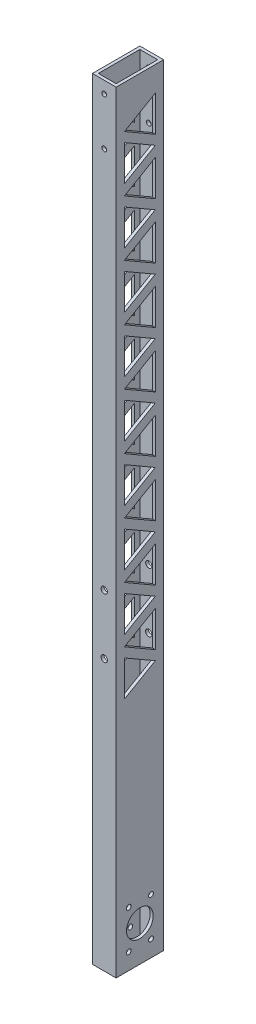
SolidWorks part; units mm, degrees
material "5052-O"
ref_plane "Front Plane" through (0, 0, 0) normal (0, 0, 1) x (1, 0, 0)
ref_plane "Top Plane" through (0, 0, 0) normal (0, 1, 0) x (1, 0, 0)
ref_plane "Right Plane" through (0, 0, 0) normal (1, 0, 0) x (0, 0, -1)
sketch "Sketch1" plane through (0, 0, 0) normal (0, 1, 0) x (1, 0, 0)
  line L0 (3.175, 3.175) -> (3.175, 47.625)
  line L1 (0, 0) -> (25.4, 0)
  line L2 (0, 0) -> (0, 50.8)
  line L3 (0, 50.8) -> (25.4, 50.8)
  line L4 (25.4, 0) -> (25.4, 50.8)
  line L5 (3.175, 47.625) -> (22.225, 47.625)
  line L6 (22.225, 3.175) -> (22.225, 47.625)
  line L7 (3.175, 3.175) -> (22.225, 3.175)
  dimension "D2" = 50.8
  dimension "D3" = 25.4
  dimension "D1" = 3.175
extrude "Boss-Extrude1" add sketch "Sketch1" along normal blind 825.5
sketch "Sketch2" plane through (0, 0, 0) normal (-1, 0, 0) x (0, 0, 1)
  line L0 (13.97, 0) -> (-13.97, 0) construction
  line L1 (-50.8, 825.5) -> (0, 825.5) construction
  circle A0 centre (-25.4, 38.1) radius 14.2875
  point P6 (-25.4, 825.5)
  dimension "D1" = 38.1
  dimension "D2" = 28.575
extrude "Cut-Extrude1" cut sketch "Sketch2" against normal through all
sketch "Sketch3" plane through (0, 0, 0) normal (0, 0, 1) x (1, 0, 0)
  line L0 (0, 825.5) -> (25.4, 825.5) construction
  line L1 (0, 825.5) -> (0, 0) construction
  circle A0 centre (12.7, 812.8) radius 2.5797
  circle A1 centre (12.7, 762) radius 2.5797
  dimension "D1" = 50.8
  dimension "D2" = 12.7
  dimension "D3" = 12.7
  dimension "D4" = 12.7
  dimension "D5" = 5.1594
  dimension "D6" = 5.1594
extrude "Cut-Extrude2" cut sketch "Sketch3" against normal through all
hole_wizard "13/64 (0.20313) Diameter Hole1" positions "Sketch4" profile "Sketch5" hole size "13/64" standard "ANSI Inch" end condition through all
sketch "Sketch4" plane through (25.4, 0, 0) normal (1, 0, 0) x (0, 0, -1)
  point P0 (37.3062, 58.7222)
  point P3 (13.4937, 58.7222)
  point P6 (37.3063, 17.4778)
  point P9 (13.4937, 17.4778)
sketch "Sketch5" plane through (25.4, 58.7222, -37.3062) normal (0, 1, 0) x (0, 0, -1)
  line L0 (0, 0) -> (0, 25.4)
  line L1 (0, 25.4) -> (2.5798, 25.4)
  line L2 (2.5798, 25.4) -> (2.5798, 0)
  line L5 (2.5798, 0) -> (0, 0)
  line L11 (0, -6.35) -> (0, 107.95) construction
  dimension "Thru Hole Dia." = 5.1595
  dimension "Thru Hole Depth" = 25.4
sketch "Sketch6" plane through (0, 0, -50.8) normal (0, 0, -1) x (-1, 0, 0)
  line L0 (-12.7, 825.5) -> (-12.7, 0) construction
  line L1 (-25.4, 825.5) -> (0, 825.5) construction
  line L2 (13.97, 0) -> (-13.97, 0) construction
  circle A0 centre (-12.7, 353.06) radius 3.3734
  circle A1 centre (-12.7, 289.56) radius 3.429
  dimension "D1" = 6.7469
  dimension "D2" = 6.858
  dimension "D4" = 63.5
  dimension "D3" = 472.44
extrude "Cut-Extrude3" cut sketch "Sketch6" against normal through all
sketch "Sketch7" plane through (25.4, 0, 0) normal (1, 0, 0) x (0, 0, -1)
  line L0 (25.4, 0) -> (25.4, 825.5) construction
  line L1 (41.91, 273.0641) -> (8.89, 292.1282)
  line L2 (8.89, 292.1282) -> (8.89, 254)
  line L3 (8.89, 254) -> (41.91, 273.0641)
  line L4 (13.97, 0) -> (-13.97, 0) construction
  line L5 (0, 825.5) -> (50.8, 825.5) construction
  line L6 (0, 0) -> (50.8, 0) construction
  line L7 (0, 825.5) -> (0, 0) construction
  line L8 (50.8, 825.5) -> (50.8, 0) construction
  line L9 (41.91, 321.4576) -> (8.89, 302.3935)
  line L10 (8.89, 302.3935) -> (41.91, 283.3294)
  line L11 (41.91, 283.3294) -> (41.91, 321.4576)
  circle A0 centre (19.8967, 273.0641) radius 11.0067 construction
  circle A1 centre (30.9033, 302.3935) radius 11.0067 construction
  point P11 (25.4, 311.9256)
  point P14 (25.4, 292.8614)
  point P16 (25.4, 282.5962)
  point P18 (25.4, 263.5321)
  dimension "D1" = 8.89
  dimension "D2" = 254
  dimension "D3" = 8.89
  dimension "D4" = 8.89
extrude "Cut-Extrude4" cut sketch "Sketch7" against normal through all
pattern_linear "LPattern1" count 9 spacing 59.69 along (0, 1, 0) of "Cut-Extrude4"
